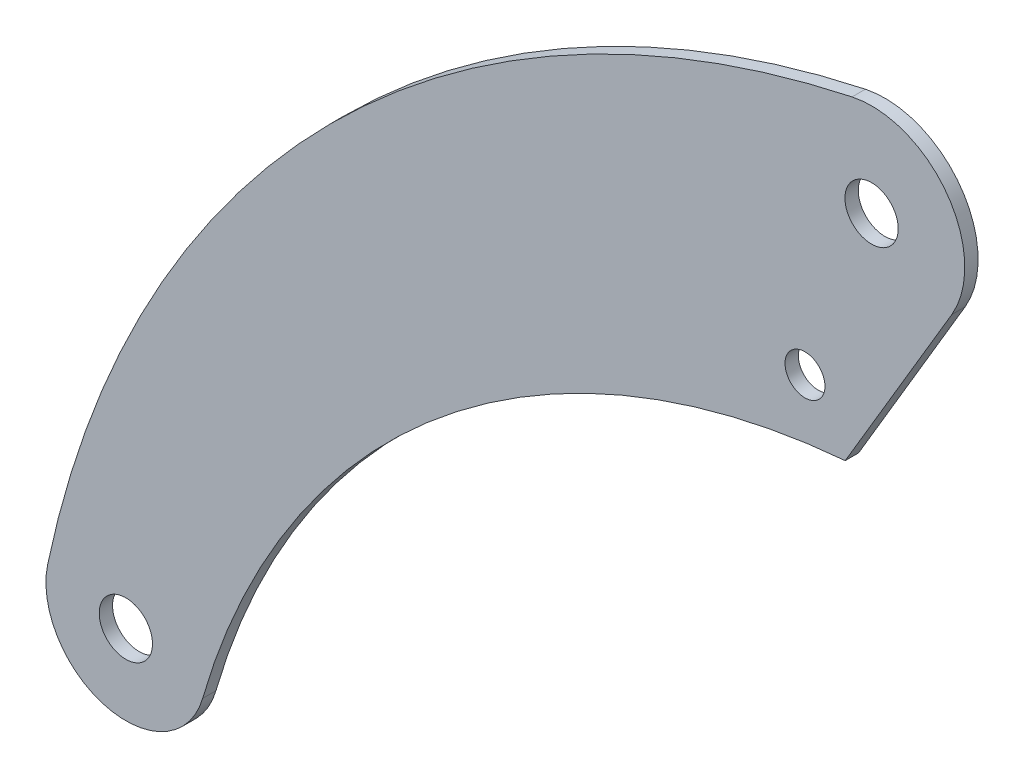
SolidWorks part; units mm, degrees
ref_plane "Front Plane" through (0, 0, 0) normal (0, 0, 1) x (1, 0, 0)
ref_plane "Top Plane" through (0, 0, 0) normal (0, 1, 0) x (1, 0, 0)
ref_plane "Right Plane" through (0, 0, 0) normal (1, 0, 0) x (0, 0, -1)
sketch "Sketch1" plane through (0, 0, 0) normal (0, 0, 1) x (1, 0, 0)
  line L1 (60.2204, -35.6862) -> (-19.7796, -170.6862)
  circle A0 centre (0, 0) radius 20
  circle A1 centre (-50, -130) radius 15
  circle A2 centre (-560, -550) radius 20
  arc A3 (-618.7157, -537.6524) -> (-502.3419, -566.5995) centre (-560, -550) ccw
  arc A4 (60.2204, -35.6862) -> (-14.6346, 68.4531) centre (0, 0) ccw
  arc A6 (-618.7157, -537.6524) -> (-14.6346, 68.4531) centre (149.4818, -699.1997) cw
  arc A7 (-502.3419, -566.5995) -> (-19.7796, -170.6862) centre (26.1907, -718.7616) cw
  dimension "D1" = 40
  dimension "D2" = 30
  dimension "D3" = 40
  dimension "D8" = 60
  dimension "D9" = 70
  dimension "D12" = 785
  dimension "D13" = 550
  dimension "D4" = 50
  dimension "D5" = 130
  dimension "D6" = 560
  dimension "D7" = 550
  dimension "D10" = 135
  dimension "D11" = 80
extrude "Boss-Extrude1" add sketch "Sketch1" along normal mid plane 10
